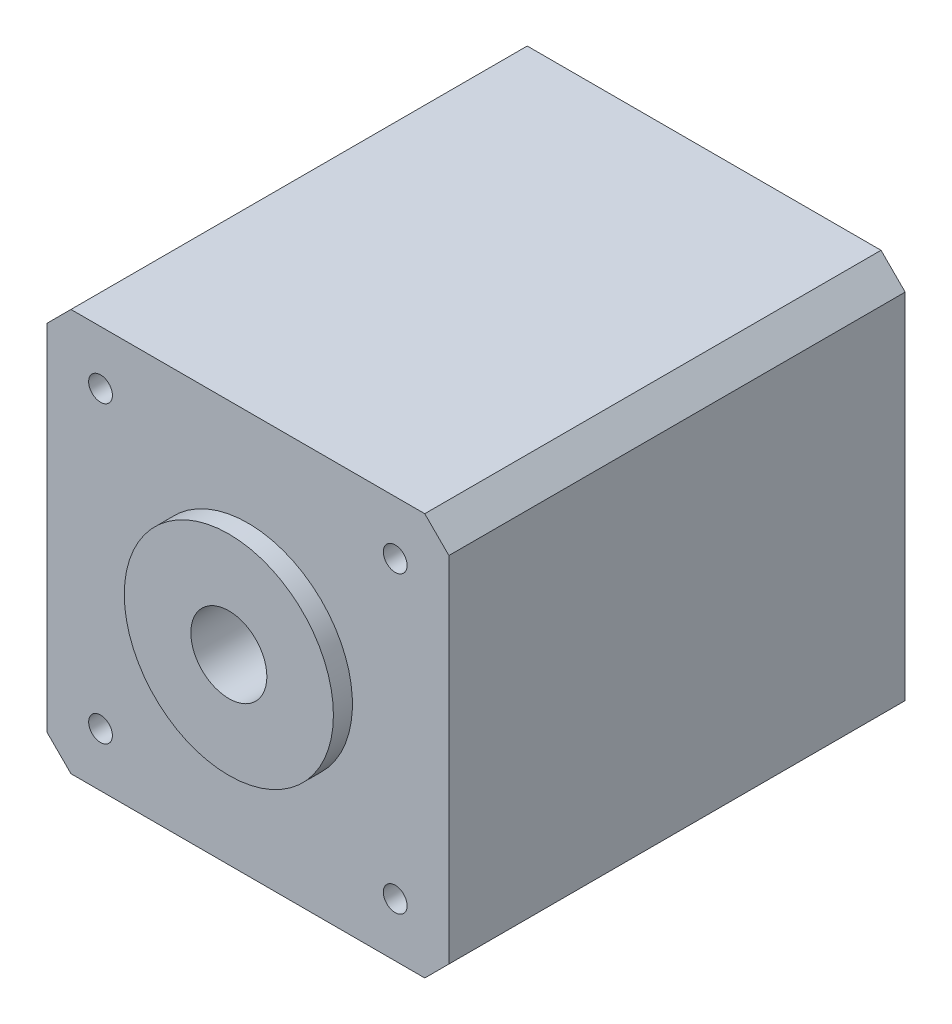
SolidWorks part; units mm, degrees
ref_plane "Front Plane" through (0, 0, 0) normal (0, 0, 1) x (1, 0, 0)
ref_plane "Top Plane" through (0, 0, 0) normal (0, 1, 0) x (1, 0, 0)
ref_plane "Right Plane" through (0, 0, 0) normal (1, 0, 0) x (0, 0, -1)
sketch "Sketch1" plane through (0, 0, 0) normal (0, 0, 1) x (1, 0, 0)
  line L1 (0, 0) -> (42.3, 0)
  line L2 (0, 0) -> (0, 42.3)
  line L3 (0, 42.3) -> (42.3, 42.3)
  line L4 (42.3, 0) -> (42.3, 42.3)
  dimension "D1" = 42.3
extrude "Boss-Extrude1" add sketch "Sketch1" along normal blind 48
hole_wizard "Tap Drill for M3x0.5 Tap1" positions "Sketch2" profile "Sketch4" hole size "M3x0.5" standard "ANSI Metric"
sketch "Sketch2" plane through (0, 0, 48) normal (0, 0, 1) x (1, 0, 0)
  line L0 (0, 42.3) -> (42.3, 0) construction
  line L3 (5.65, 5.65) -> (36.65, 5.65) construction
  line L4 (5.65, 5.65) -> (5.65, 36.65) construction
  line L5 (5.65, 36.65) -> (36.65, 36.65) construction
  line L6 (36.65, 5.65) -> (36.65, 36.65) construction
  line L7 (5.65, 5.65) -> (36.65, 36.65) construction
  line L8 (5.65, 36.65) -> (36.65, 5.65) construction
  point P8 (36.65, 36.65)
  point P55 (5.65, 5.65)
  point P56 (5.65, 36.65)
  point P57 (36.65, 5.65)
  dimension "D1" = 31
sketch "Sketch4" plane through (36.65, 5.65, 48) normal (1, 0, 0) x (0, -1, 0)
  line L0 (0, 0) -> (0, 8.6191)
  line L1 (0, 8.6191) -> (1.25, 7.868)
  line L2 (1.25, 7.868) -> (1.25, 0)
  line L5 (1.25, 0) -> (0, 0)
  line L10 (0, 8.6191) -> (-1.25, 7.868) construction
  line L11 (0, -6.35) -> (0, 107.95) construction
  dimension "Hole Dia." = 2.5
  dimension "Hole Depth" = 7.868
  dimension "Drill Angle" = 118
sketch "Sketch5" plane through (0, 0, 48) normal (0, 0, 1) x (1, 0, 0)
  line L0 (0, 42.3) -> (42.3, 0) construction
  circle A0 centre (21.15, 21.15) radius 11
  dimension "D1" = 22
extrude "Boss-Extrude2" add sketch "Sketch5" along normal blind 2
sketch "Sketch6" plane through (0, 0, 50) normal (0, 0, 1) x (1, 0, 0)
  circle A0 centre (21.15, 21.15) radius 4
  dimension "D1" = 8
extrude "Cut-Extrude1" cut sketch "Sketch6" against normal through all
chamfer "Chamfer1" distance 2.54 angle 45 4 edges at (42.3, 0, 24) (0, 0, 24) (0, 42.3, 24) (42.3, 42.3, 24)
